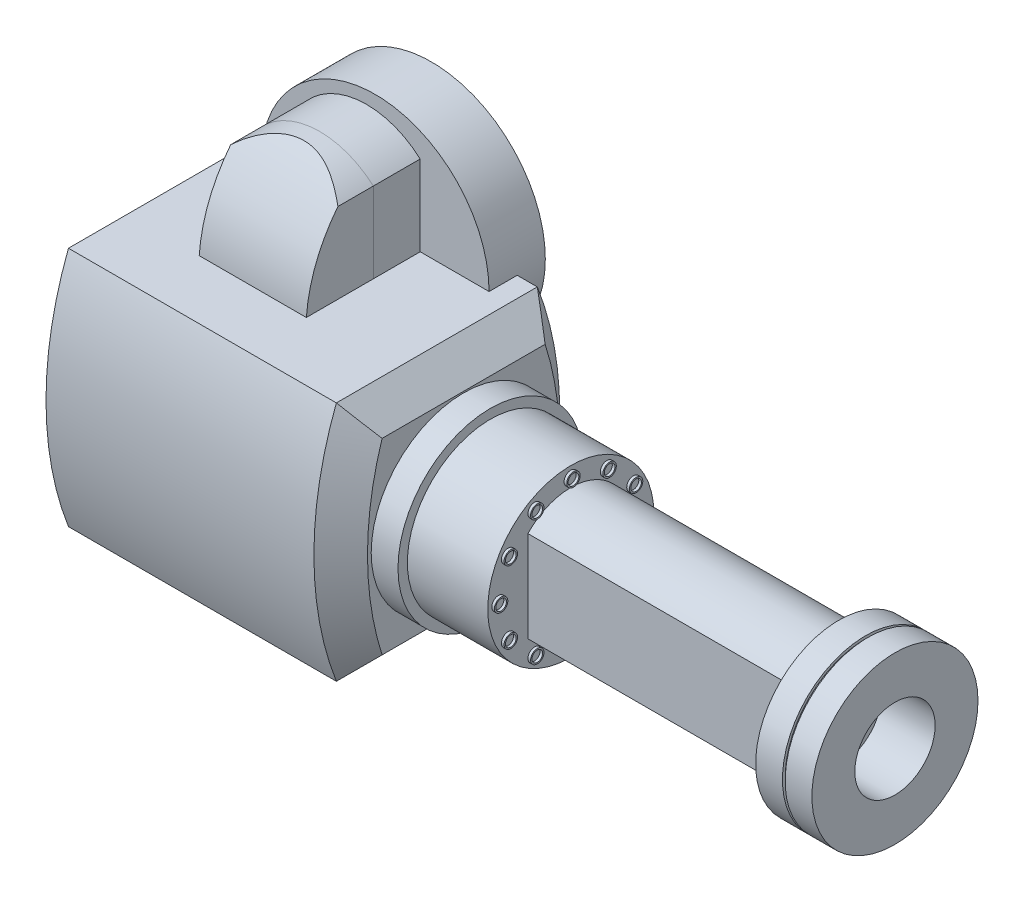
SolidWorks part; units mm, degrees
ref_plane "Front Plane" through (0, 0, 0) normal (0, 0, 1) x (1, 0, 0)
ref_plane "Top Plane" through (0, 0, 0) normal (0, 1, 0) x (1, 0, 0)
ref_plane "Right Plane" through (0, 0, 0) normal (1, 0, 0) x (0, 0, -1)
sketch "Sketch1" plane through (0, 0, 0) normal (1, 0, 0) x (0, 0, -1)
  line L0 (0, 0) -> (-179.5522, 0) construction
  line L1 (0, 0) -> (131.3015, 0) construction
  line L2 (0, 0) -> (0, -111.8732) construction
  line L3 (0, 0) -> (0, 106.3222) construction
  line L4 (-37.5, 45) -> (37.5, 45)
  line L5 (-37.5, -45) -> (37.5, -45)
  arc A0 (37.5, 45) -> (37.5, -45) centre (-79.119, 0) cw
  arc A1 (-37.5, 45) -> (-37.5, -45) centre (79.119, 0) ccw
  point P12 (0, -45)
  point P14 (0, 45)
  dimension "D1" = 125
  dimension "D2" = 45
  dimension "D3" = 45
  dimension "D4" = 37.5
  dimension "D5" = 37.5
extrude "Boss-Extrude1" add sketch "Sketch1" along normal blind 100
sketch "Sketch4" plane through (100, 0, 0) normal (1, 0, 0) x (0, 0, -1)
  line L2 (37.5, 45) -> (-37.5, 45)
  line L3 (-37.5, -45) -> (37.5, -45)
  line L4 (37.5, 45) -> (-37.5, 45)
  line L5 (-37.5, -45) -> (37.5, -45)
  arc A2 (37.5, -45) -> (37.5, 45) centre (-79.119, 0) ccw
  arc A3 (-37.5, 45) -> (-37.5, -45) centre (79.119, 0) ccw
  arc A4 (37.5, -45) -> (37.5, 45) centre (-79.119, 0) ccw
  arc A5 (-37.5, 45) -> (-37.5, -45) centre (79.119, 0) ccw
  dimension "D1" = 0
extrude "Boss-Extrude2" add sketch "Sketch4" along normal blind 10 draft 45 separate body
sketch "Sketch5" plane through (110, 0, 0) normal (1, 0, 0) x (0, 0, -1)
  circle A0 centre (0, 0) radius 34.5
  dimension "D1" = 69
extrude "Boss-Extrude3" add sketch "Sketch5" along normal blind 10 separate body
sketch "Sketch6" plane through (120, 0, 0) normal (1, 0, 0) x (0, 0, -1)
  circle A0 centre (0, 0) radius 31
  dimension "D1" = 62
extrude "Boss-Extrude4" add sketch "Sketch6" along normal blind 30
sketch "Sketch7" plane through (150, 0, 0) normal (1, 0, 0) x (0, 0, -1)
  circle A0 centre (27, 0) radius 2
  circle A1 centre (27, 0) radius 2.5
  dimension "D1" = 4
  dimension "D3" = 5
  dimension "D2" = 27
extrude "Boss-Extrude5" add sketch "Sketch7" along normal blind 1
pattern_circular "CirPattern1" count 12 over 360 about axis through (0, 0, 0) along (1, 0, 0) of "Boss-Extrude5"
sketch "Sketch9" plane through (150, 0, 0) normal (1, 0, 0) x (0, 0, -1)
  line L0 (0, 0) -> (0, 19.4063) construction
  line L1 (0, 0) -> (0, -19.4297) construction
  line L2 (-19.7802, 0) -> (20.2194, 0) construction
  line L3 (16, -17) -> (16, 17)
  line L4 (-16, -17) -> (-16, 17)
  arc A0 (-16, 17) -> (16, 17) centre (0, 1.9003) cw
  arc A1 (-16, -17) -> (16, -17) centre (0, -1.9003) ccw
  point P9 (16, 0)
  dimension "D3" = 22
  dimension "D1" = 16
  dimension "D2" = 17
extrude "Boss-Extrude6" add sketch "Sketch9" along normal blind 100
sketch "Sketch10" plane through (250, 0, 0) normal (1, 0, 0) x (0, 0, -1)
  circle A0 centre (0, 0) radius 31
extrude "Boss-Extrude7" add sketch "Sketch10" along normal blind 10
sketch "Sketch11" plane through (260, 0, 0) normal (1, 0, 0) x (0, 0, -1)
  circle A0 centre (0, 0) radius 30
  circle A1 centre (0, 0) radius 31 construction
  dimension "D1" = 1
extrude "Boss-Extrude8" add sketch "Sketch11" along normal blind 1
sketch "Sketch12" plane through (261, 0, 0) normal (1, 0, 0) x (0, 0, -1)
  circle A0 centre (0, 0) radius 31
extrude "Boss-Extrude9" add sketch "Sketch12" along normal blind 10
ref_plane "Plane1" through (0, 0, -37.5) normal (0, 0, 1) x (1, 0, 0)
sketch "Sketch13" plane through (0, 0, -37.5) normal (0, 0, 1) x (1, 0, 0)
  line L0 (100, 45) -> (0, 45) construction
  circle A0 centre (50, 45) radius 42.5
  dimension "D1" = 85
extrude "Boss-Extrude10" add sketch "Sketch13" against normal mid plane 21 separate body
sketch "Sketch16" plane through (0, 0, -27) normal (0, 0, 1) x (1, 0, 0)
  line L0 (26.7966, 45) -> (66.7966, 45)
  line L2 (26.7966, 45) -> (26.7966, 75)
  line L3 (66.7966, 45) -> (66.7966, 75)
  arc A0 (26.7966, 75) -> (66.7966, 75) centre (46.7966, 52.6393) cw
  point P4 (46.7966, 45)
  dimension "D4" = 30
  dimension "D1" = 40
  dimension "D2" = 30
  dimension "D3" = 30
extrude "Boss-Extrude11" add sketch "Sketch16" along normal mid plane 35
sketch "Sketch17" plane through (66.7966, 0, 0) normal (1, 0, 0) x (0, 0, -1)
  line L0 (9.5, 45) -> (9.5, 87)
  line L1 (9.5, 45) -> (-15.5, 45)
  line L2 (37.5, 45) -> (-37.5, 45) construction
  arc A0 (-15.5, 45) -> (9.5, 87) centre (39.3393, 40.7981) cw
  dimension "D3" = 55
  dimension "D1" = 25
  dimension "D2" = 42
extrude "Boss-Extrude15" add sketch "Sketch17" against normal blind 40 separate body
sketch "Sketch24" plane through (0, 0, -9.5) normal (0, 0, -1) x (-1, 0, 0)
  line L0 (-26.7966, 75) -> (-26.7966, 95.3759)
  line L1 (-26.7966, 95.3759) -> (-66.7966, 96.1082)
  line L2 (-66.7966, 96.1082) -> (-66.7966, 75)
  arc A0 (-26.7966, 75) -> (-66.7966, 75) centre (-46.7966, 52.6393) ccw
extrude "Cut-Extrude2" cut sketch "Sketch24" against normal blind 40
sketch "Sketch25" plane through (271, 0, 0) normal (1, 0, 0) x (0, 0, -1)
  circle A0 centre (0, 0) radius 15
  dimension "D1" = 30
extrude "Cut-Extrude3" cut sketch "Sketch25" against normal blind 20
sketch "Sketch26" plane through (0, 0, -48) normal (0, 0, -1) x (-1, 0, 0)
  circle A2 centre (-50, 45) radius 12.5
  circle A3 centre (-50, 45) radius 42.5 construction
  dimension "D1" = 30
extrude "Cut-Extrude4" cut sketch "Sketch26" against normal blind 20
